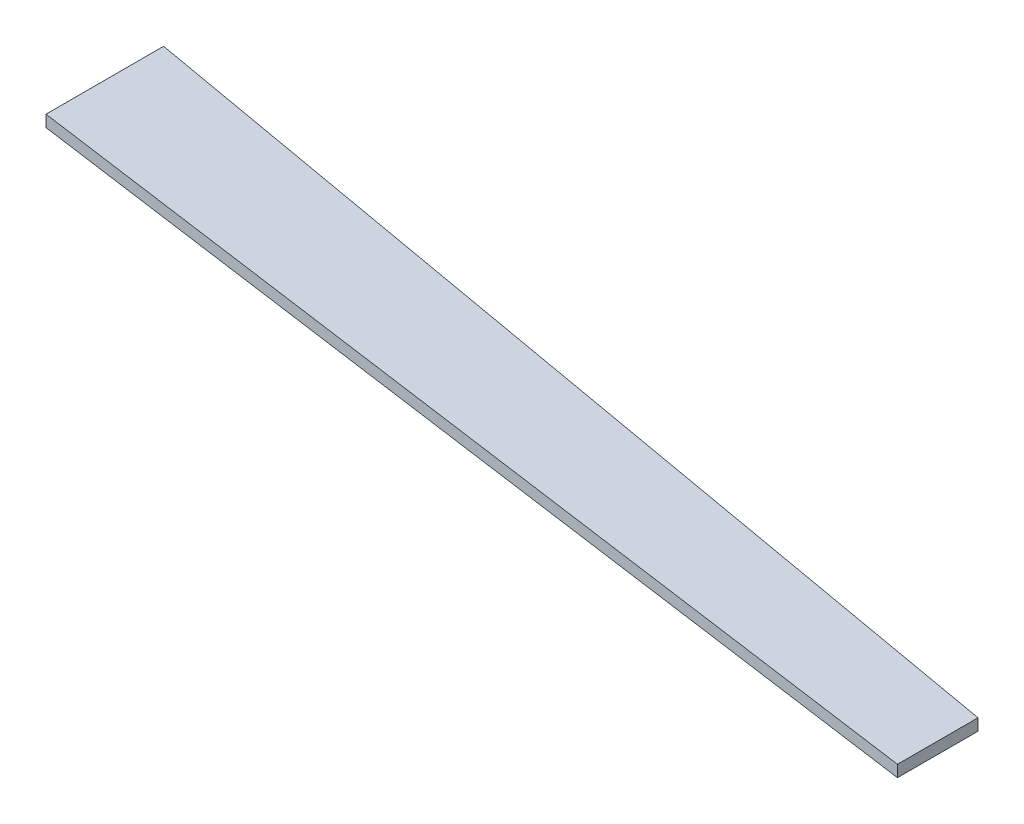
SolidWorks part; units mm, degrees
ref_plane "Front Plane" through (0, 0, 0) normal (0, 0, 1) x (1, 0, 0)
ref_plane "Top Plane" through (0, 0, 0) normal (0, 1, 0) x (1, 0, 0)
ref_plane "Right Plane" through (0, 0, 0) normal (1, 0, 0) x (0, 0, -1)
sketch "Sketch1" plane through (0, 0, 0) normal (0, 1, 0) x (1, 0, 0)
  line L0 (-65.4913, 13.248) -> (-65.4913, 33.468)
  line L1 (-65.4913, 33.468) -> (104.5063, 3.4928)
  line L2 (104.5063, 3.4928) -> (104.5063, -10.3572)
  line L3 (104.5063, -10.3572) -> (-65.4913, 13.248)
  dimension "D1" = 20.22
  dimension "D2" = 13.85
  dimension "D3" = 172.62
  dimension "D4" = 80
extrude "Boss-Extrude1" add sketch "Sketch1" along normal blind 2
chamfer "Chamfer1" [suppressed] distance 2 angle 45
